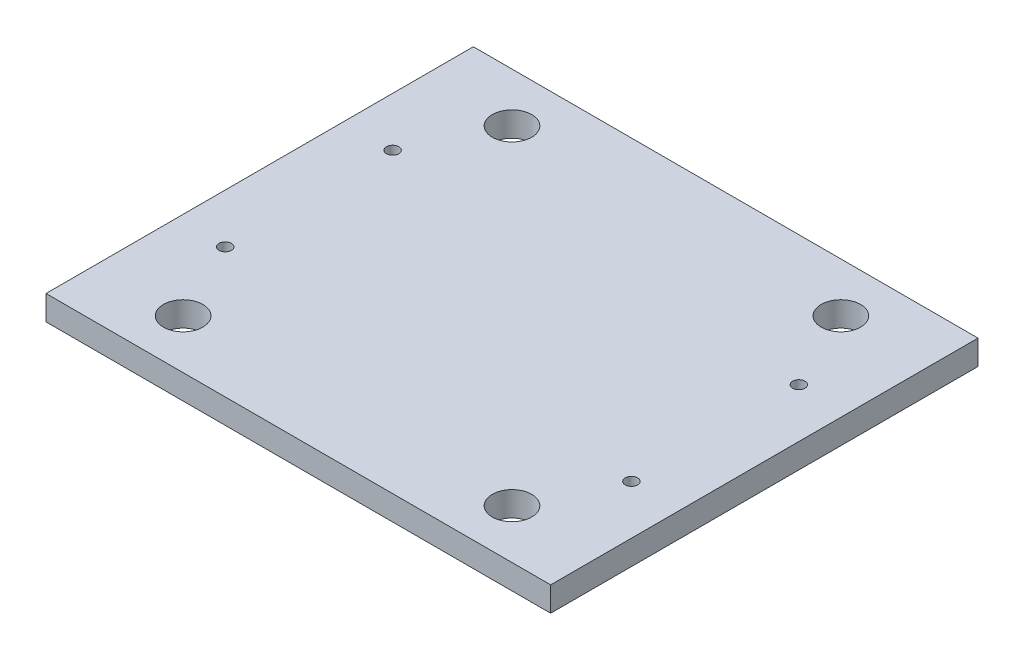
SolidWorks part; units mm, degrees
ref_plane "Front Plane" through (0, 0, 0) normal (0, 0, 1) x (1, 0, 0)
ref_plane "Top Plane" through (0, 0, 0) normal (0, 1, 0) x (1, 0, 0)
ref_plane "Right Plane" through (0, 0, 0) normal (1, 0, 0) x (0, 0, -1)
sketch "Sketch1" plane through (0, 0, 0) normal (0, 1, 0) x (1, 0, 0)
  line L1 (-52.3875, -21.59) -> (52.3875, -21.59) construction
  line L2 (-52.3875, -21.59) -> (-52.3875, 21.59) construction
  line L3 (-52.3875, 21.59) -> (52.3875, 21.59) construction
  line L4 (52.3875, -21.59) -> (52.3875, 21.59) construction
  line L5 (-52.3875, -21.59) -> (52.3875, 21.59) construction
  line L6 (-52.3875, 21.59) -> (52.3875, -21.59) construction
  line L7 (-42.418, -42.418) -> (42.418, -42.418) construction
  line L8 (-42.418, -42.418) -> (-42.418, 42.418) construction
  line L9 (-42.418, 42.418) -> (42.418, 42.418) construction
  line L10 (42.418, -42.418) -> (42.418, 42.418) construction
  line L11 (-42.418, -42.418) -> (42.418, 42.418) construction
  line L12 (-42.418, 42.418) -> (42.418, -42.418) construction
  line L13 (-65.0875, -55.118) -> (65.0875, -55.118)
  line L14 (-65.0875, -55.118) -> (-65.0875, 55.118)
  line L15 (-65.0875, 55.118) -> (65.0875, 55.118)
  line L16 (65.0875, -55.118) -> (65.0875, 55.118)
  line L17 (-65.0875, -55.118) -> (65.0875, 55.118) construction
  line L18 (-65.0875, 55.118) -> (65.0875, -55.118) construction
  circle A0 centre (-52.3875, 21.59) radius 1.5875
  circle A1 centre (52.3875, 21.59) radius 1.5875
  circle A2 centre (52.3875, -21.59) radius 1.5875
  circle A3 centre (-52.3875, -21.59) radius 1.5875
  circle A4 centre (-42.418, 42.418) radius 5.08
  circle A5 centre (42.418, 42.418) radius 5.08
  circle A6 centre (42.418, -42.418) radius 5.08
  circle A7 centre (-42.418, -42.418) radius 5.08
  point P0 (0, 0)
  point P10 (0, 0)
  point P19 (0, 0)
  dimension "D1" = 3.175
  dimension "D4" = 10.16
  dimension "D2" = 104.775
  dimension "D3" = 43.18
  dimension "D5" = 84.836
  dimension "D6" = 12.7
  dimension "D7" = 12.7
extrude "Boss-Extrude1" add sketch "Sketch1" along normal blind 6.35
